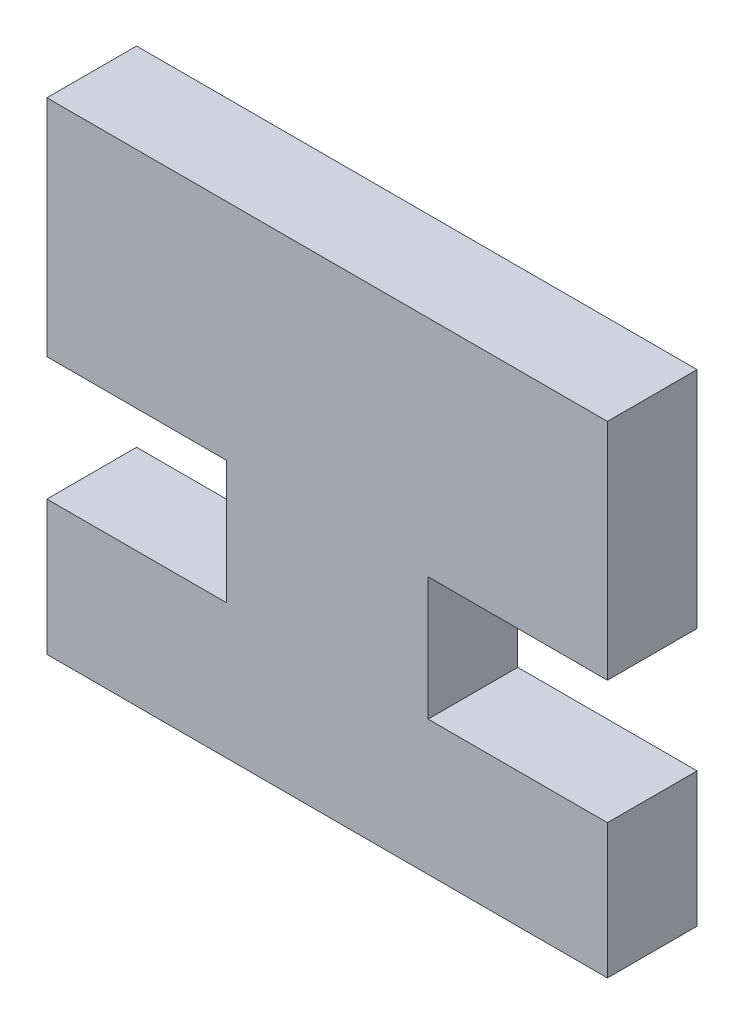
SolidWorks part; units mm, degrees
ref_plane "Front Plane" through (0, 0, 0) normal (0, 0, 1) x (1, 0, 0)
ref_plane "Top Plane" through (0, 0, 0) normal (0, 1, 0) x (1, 0, 0)
ref_plane "Right Plane" through (0, 0, 0) normal (1, 0, 0) x (0, 0, -1)
sketch "Sketch1" plane through (0, 0, 0) normal (0, 0, 1) x (1, 0, 0)
  line L0 (-83.1719, 24.3044) -> (-58.1719, 24.3044)
  line L1 (-75.1719, 14.3044) -> (-66.1719, 14.3044) construction
  line L2 (-83.1719, 24.3044) -> (-83.1719, 14.3044)
  line L3 (-83.1719, 14.3044) -> (-75.1719, 14.3044)
  line L5 (-83.1719, 8.8044) -> (-75.1719, 8.8044)
  line L6 (-83.1719, 8.8044) -> (-83.1719, 2.8044)
  line L7 (-83.1719, 2.8044) -> (-58.1719, 2.8044)
  line L10 (-75.1719, 14.3044) -> (-75.1719, 8.8044)
  line L12 (-66.1719, 14.3044) -> (-66.1719, 8.8044)
  line L13 (-66.1719, 14.3044) -> (-58.1719, 14.3044)
  line L16 (-58.1719, 14.3044) -> (-58.1719, 24.3044)
  line L17 (-66.1719, 8.8044) -> (-58.1719, 8.8044)
  line L20 (-58.1719, 8.8044) -> (-58.1719, 2.8044)
  dimension "D1" = 8
extrude "Boss-Extrude1" add sketch "Sketch1" along normal blind 4
